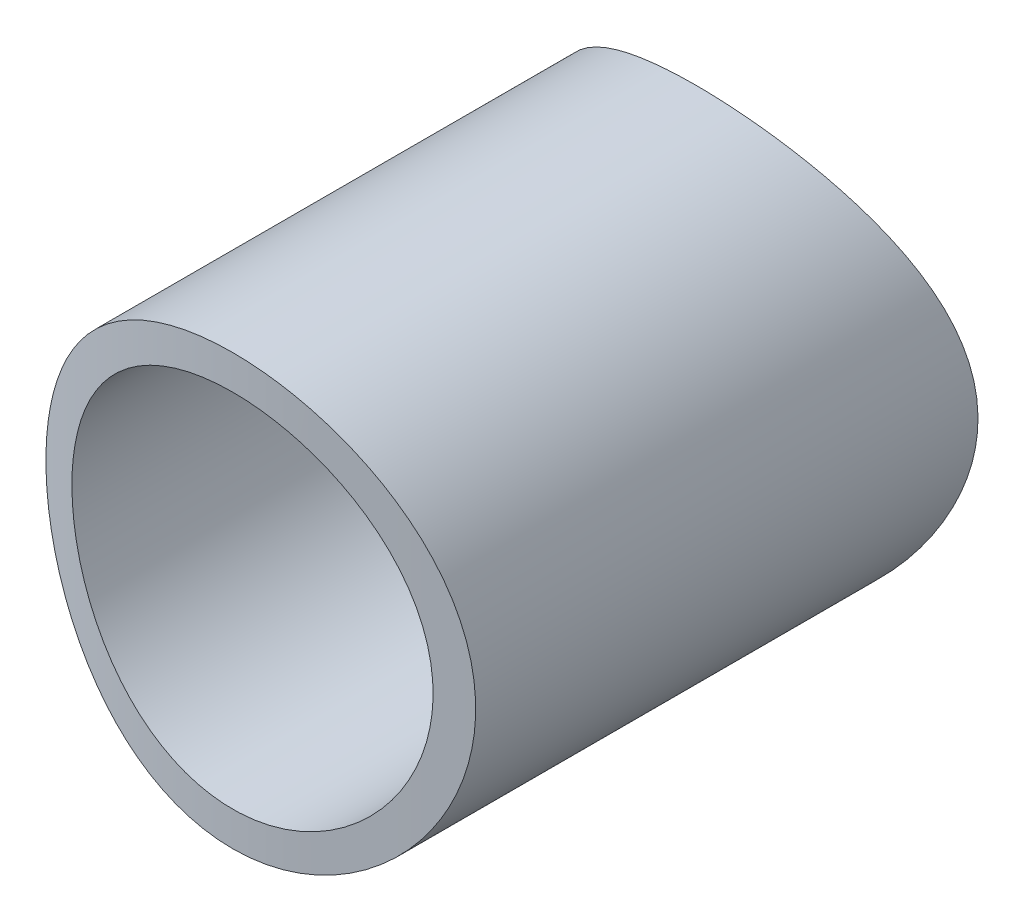
SolidWorks part; units mm, degrees
material "PTFE (general)"
ref_plane "Front Plane" through (0, 0, 0) normal (0, 0, 1) x (1, 0, 0)
ref_plane "Top Plane" through (0, 0, 0) normal (0, 1, 0) x (1, 0, 0)
ref_plane "Right Plane" through (0, 0, 0) normal (1, 0, 0) x (0, 0, -1)
sketch "Sketch1" plane through (0, 0, 0) normal (0, 0, 1) x (1, 0, 0)
  circle A0 centre (0, 0) radius 10.53
  circle A1 centre (0, 0) radius 12.53
  dimension "D1" = 21.06
  dimension "D2" = 2
extrude "Boss-Extrude1" add sketch "Sketch1" along normal blind 60
sketch "Sketch2" plane through (0, 0, 0) normal (0, 1, 0) x (1, 0, 0)
  circle A0 centre (0, 0) radius 22
  circle A1 centre (0, 0) radius 49
  circle A2 centre (0, 0) radius 74.5897
  dimension "D1" = 44
  dimension "D2" = 98
extrude "Cut-Extrude1" cut sketch "Sketch2" against normal through all both and the other way through all contours A2 A1 | A0
